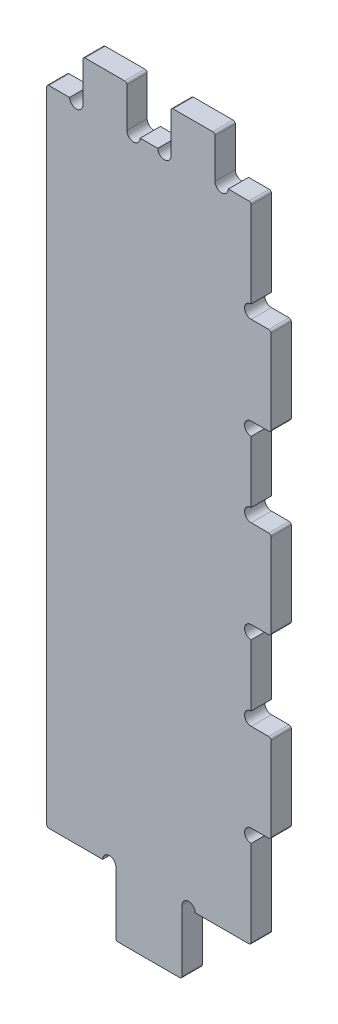
SolidWorks part; units mm, degrees
material "POM Acetal Copolymer"
ref_plane "Front Plane" through (0, 0, 0) normal (0, 0, 1) x (1, 0, 0)
ref_plane "Top Plane" through (0, 0, 0) normal (0, 1, 0) x (1, 0, 0)
ref_plane "Right Plane" through (0, 0, 0) normal (1, 0, 0) x (0, 0, -1)
sketch "Sketch1" plane through (0, 0, 0) normal (0, 0, 1) x (1, 0, 0)
  line L0 (8.2, 146) -> (8.2, 155.5)
  line L1 (0, 0) -> (15.7, 0)
  line L2 (0, 0) -> (0, 146)
  line L3 (0, 146) -> (8.2, 146)
  line L4 (46.4, 0) -> (46.4, 23)
  line L5 (8.2, 155.5) -> (18.2, 155.5)
  line L6 (18.2, 155.5) -> (18.2, 146)
  line L7 (18.2, 146) -> (28.2, 146)
  line L8 (8.2, 146) -> (18.2, 146) construction
  line L9 (23.2, -14.5) -> (23.2, 146) construction
  line L10 (15.7, 0) -> (15.7, -14.5)
  line L11 (15.7, -14.5) -> (30.7, -14.5)
  line L12 (30.7, -14.5) -> (30.7, 0)
  line L13 (30.7, 0) -> (46.4, 0)
  line L14 (15.7, 0) -> (30.7, 0) construction
  line L15 (38.2, 146) -> (28.2, 146) construction
  line L16 (28.2, 155.5) -> (28.2, 146)
  line L17 (38.2, 155.5) -> (28.2, 155.5)
  line L18 (38.2, 146) -> (38.2, 155.5)
  line L19 (38.2, 146) -> (46.4, 146)
  line L20 (46.4, 123) -> (50.9, 123)
  line L21 (50.9, 123) -> (50.9, 103)
  line L22 (50.9, 103) -> (46.4, 103)
  line L23 (46.4, 83) -> (50.9, 83)
  line L24 (50.9, 83) -> (50.9, 63)
  line L25 (50.9, 63) -> (46.4, 63)
  line L26 (46.4, 43) -> (50.9, 43)
  line L27 (50.9, 43) -> (50.9, 23)
  line L28 (50.9, 23) -> (46.4, 23)
  line L29 (46.4, 123) -> (46.4, 146)
  line L30 (46.4, 83) -> (46.4, 103)
  line L31 (46.4, 43) -> (46.4, 63)
  dimension "D1" = 46.4
  dimension "D2" = 146
  dimension "D3" = 14.5
  dimension "D4" = 15
  dimension "D5" = 10
  dimension "D6" = 10
  dimension "D7" = 9.5
  dimension "D8" = 20
  dimension "D9" = 23
  dimension "D10" = 20
  dimension "D11" = 20
  dimension "D12" = 23
  dimension "D13" = 4.5
extrude "Boss-Extrude1" add sketch "Sketch1" along normal blind 4.6
sketch "Sketch2" plane through (0, 0, 4.6) normal (0, 0, 1) x (1, 0, 0)
  line L0 (14.2, 0) -> (14.2, -5) construction
  line L1 (0, 0) -> (15.7, 0) construction
  line L2 (15.7, 0) -> (15.7, -5)
  line L3 (12.7, 0) -> (12.7, -5)
  line L4 (15.7, 0) -> (15.7, -14.5) construction
  line L5 (23.2, -14.5) -> (23.2, 146) construction
  line L6 (15.7, -14.5) -> (30.7, -14.5) construction
  line L7 (28.2, 146) -> (18.2, 146) construction
  line L8 (32.2, 0) -> (32.2, -5) construction
  line L9 (30.7, 0) -> (30.7, -5)
  line L10 (33.7, 0) -> (33.7, -5)
  line L11 (50.9, 33) -> (35.779, 33) construction
  line L12 (50.9, 23) -> (50.9, 43) construction
  line L13 (50.9, 73) -> (35.779, 73) construction
  line L14 (50.9, 63) -> (50.9, 83) construction
  line L15 (50.9, 113) -> (35.779, 113) construction
  line L16 (50.9, 103) -> (50.9, 123) construction
  line L17 (46.4, 21.5) -> (50.9, 21.5) construction
  line L18 (46.4, 0) -> (46.4, 23) construction
  line L19 (46.4, 23) -> (50.9, 23)
  line L20 (46.4, 20) -> (50.9, 20)
  line L21 (46.4, 61.5) -> (50.9, 61.5) construction
  line L22 (46.4, 43) -> (46.4, 63) construction
  line L23 (46.4, 63) -> (50.9, 63)
  line L24 (46.4, 60) -> (50.9, 60)
  line L25 (46.4, 101.5) -> (50.9, 101.5) construction
  line L26 (46.4, 83) -> (46.4, 103) construction
  line L27 (46.4, 103) -> (50.9, 103)
  line L28 (46.4, 100) -> (50.9, 100)
  line L29 (46.4, 23) -> (50.9, 23) construction
  line L30 (46.4, 44.5) -> (50.9, 44.5) construction
  line L31 (46.4, 43) -> (50.9, 43)
  line L32 (46.4, 46) -> (50.9, 46)
  line L33 (46.4, 84.5) -> (50.9, 84.5) construction
  line L34 (46.4, 83) -> (50.9, 83)
  line L35 (46.4, 86) -> (50.9, 86)
  line L36 (46.4, 124.5) -> (50.9, 124.5) construction
  line L37 (46.4, 123) -> (50.9, 123)
  line L38 (46.4, 126) -> (50.9, 126)
  line L39 (33.2, 155.5) -> (33.2, 144.8273) construction
  line L40 (38.2, 155.5) -> (28.2, 155.5) construction
  line L41 (39.7, 146) -> (39.7, 155.5) construction
  line L42 (46.4, 146) -> (38.2, 146) construction
  line L43 (38.2, 146) -> (38.2, 155.5)
  line L44 (41.2, 146) -> (41.2, 155.5)
  line L45 (38.2, 146) -> (38.2, 155.5) construction
  line L46 (26.7, 146) -> (26.7, 155.5) construction
  line L47 (28.2, 146) -> (28.2, 155.5)
  line L48 (25.2, 146) -> (25.2, 155.5)
  line L49 (6.7, 146) -> (6.7, 155.5) construction
  line L50 (8.2, 146) -> (8.2, 155.5)
  line L51 (5.2, 146) -> (5.2, 155.5)
  line L52 (19.7, 146) -> (19.7, 155.5) construction
  line L53 (18.2, 146) -> (18.2, 155.5)
  line L54 (21.2, 146) -> (21.2, 155.5)
  arc A0 (15.7, 0) -> (12.7, 0) centre (14.2, 0) ccw
  arc A1 (12.7, -5) -> (15.7, -5) centre (14.2, -5) ccw
  arc A2 (30.7, 0) -> (33.7, 0) centre (32.2, 0) cw
  arc A3 (33.7, -5) -> (30.7, -5) centre (32.2, -5) cw
  arc A4 (46.4, 23) -> (46.4, 20) centre (46.4, 21.5) ccw
  arc A5 (50.9, 20) -> (50.9, 23) centre (50.9, 21.5) ccw
  arc A6 (46.4, 63) -> (46.4, 60) centre (46.4, 61.5) ccw
  arc A7 (50.9, 60) -> (50.9, 63) centre (50.9, 61.5) ccw
  arc A8 (46.4, 103) -> (46.4, 100) centre (46.4, 101.5) ccw
  arc A9 (50.9, 100) -> (50.9, 103) centre (50.9, 101.5) ccw
  arc A10 (46.4, 43) -> (46.4, 46) centre (46.4, 44.5) cw
  arc A11 (50.9, 46) -> (50.9, 43) centre (50.9, 44.5) cw
  arc A12 (46.4, 83) -> (46.4, 86) centre (46.4, 84.5) cw
  arc A13 (50.9, 86) -> (50.9, 83) centre (50.9, 84.5) cw
  arc A14 (46.4, 123) -> (46.4, 126) centre (46.4, 124.5) cw
  arc A15 (50.9, 126) -> (50.9, 123) centre (50.9, 124.5) cw
  arc A16 (38.2, 146) -> (41.2, 146) centre (39.7, 146) ccw
  arc A17 (41.2, 155.5) -> (38.2, 155.5) centre (39.7, 155.5) ccw
  arc A18 (28.2, 146) -> (25.2, 146) centre (26.7, 146) cw
  arc A19 (25.2, 155.5) -> (28.2, 155.5) centre (26.7, 155.5) cw
  arc A20 (8.2, 146) -> (5.2, 146) centre (6.7, 146) cw
  arc A21 (5.2, 155.5) -> (8.2, 155.5) centre (6.7, 155.5) cw
  arc A22 (18.2, 146) -> (21.2, 146) centre (19.7, 146) ccw
  arc A23 (21.2, 155.5) -> (18.2, 155.5) centre (19.7, 155.5) ccw
  point P6 (14.2, -2.5)
  point P14 (48.65, 44.5)
  point P28 (32.2, -2.5)
  point P51 (48.65, 21.5)
  point P56 (48.65, 61.5)
  point P65 (48.65, 101.5)
  point P74 (48.65, 84.5)
  point P85 (48.65, 124.5)
  point P98 (39.7, 150.75)
  point P107 (26.7, 150.75)
  point P114 (6.7, 150.75)
  point P121 (19.7, 150.75)
  dimension "D1" = 3
  dimension "D2" = 5
extrude "Cut-Extrude1" cut sketch "Sketch2" against normal through all
fillet "Fillet1" radius 0.5 16 edges at (0, 0, 2.3) (46.4, 0, 2.3) (30.7, -14.5, 2.3) (15.7, -14.5, 2.3) (8.2, 155.5, 2.3) (28.2, 155.5, 2.3) (18.2, 155.5, 2.3) (38.2, 155.5, 2.3) (0, 146, 2.3) (50.9, 23, 2.3) (50.9, 43, 2.3) (50.9, 63, 2.3) (50.9, 83, 2.3) (50.9, 103, 2.3) (50.9, 123, 2.3) (46.4, 146, 2.3)
